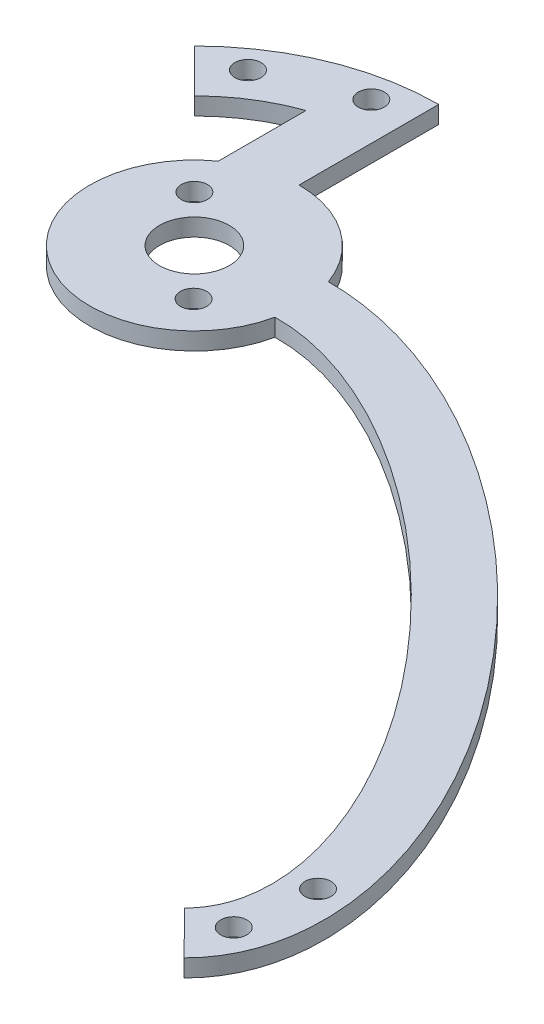
SolidWorks part; units mm, degrees
ref_plane "Спереди" through (0, 0, 0) normal (0, 0, 1) x (1, 0, 0)
ref_plane "Сверху" through (0, 0, 0) normal (0, 1, 0) x (1, 0, 0)
ref_plane "Справа" through (0, 0, 0) normal (1, 0, 0) x (0, 0, -1)
sketch "Эскиз1" plane through (0, 0, 0) normal (0, 1, 0) x (1, 0, 0)
  line L0 (0, 22) -> (0, 28)
  line L1 (65.2044, -66.3128) -> (70.1122, -71.3041)
  line L2 (0, 0) -> (-33.0408, 33.0408) construction
  line L3 (0, 12) -> (0, 22)
  line L4 (-14.8492, 14.8492) -> (-19.799, 19.799)
  line L5 (-7, 19.799) -> (-7, 9.7468)
  line L11 (0, 0) -> (70.1122, -71.3041) construction
  arc A0 (0, 28) -> (-19.799, 19.799) centre (0, 0) ccw
  arc A1 (-7, 19.799) -> (-14.8492, 14.8492) centre (0, 0) ccw
  circle A2 centre (0, 0) radius 7.5 construction
  arc A3 (-7, 9.7468) -> (11.7369, -2.4988) centre (0, 0) ccw
  arc A4 (11.2868, 4.0752) -> (0, 12) centre (0, 0) ccw
  circle A5 centre (0, 0) radius 4
  circle A6 centre (-5.3033, 5.3033) radius 1.5
  circle A7 centre (5.2584, -5.3478) radius 1.5
  ellipse E1 centre (35.0561, -35.6521) end of major axis (4.9079, -4.9913) minor radius 18 (65.2044, -66.3128) -> (11.7369, -2.4988) ccw
  ellipse E2 centre (35.0561, -35.6521) end of major axis (70.1122, -71.3041) minor radius 25 (70.1122, -71.3041) -> (11.2868, 4.0752) ccw
  dimension "D1" = 28
  dimension "D2" = 21
  dimension "D7" = 24
  dimension "D4" = 8
  dimension "D3" = 50
  dimension "D5" = 7
  dimension "D8" = 7
extrude "Бобышка-Вытянуть1" add sketch "Эскиз1" along normal blind 2
sketch "Эскиз2" plane through (0, 2, 0) normal (0, 1, 0) x (1, 0, 0)
  line L0 (0, 0) -> (0, 16.5609) construction
  line L1 (0, 0) -> (-2.989, 16.9517) construction
  line L2 (0, 0) -> (-6.9675, 16.8209) construction
  line L3 (0, 0) -> (70.1122, -71.3041) construction
  line L5 (35.0561, -35.6521) -> (89.9937, -82.5448) construction
  line L6 (35.0561, -35.6521) -> (104.5272, -76.5457) construction
  circle A0 centre (0, 0) radius 25 construction
  circle A1 centre (-4.3412, 24.6202) radius 1.5
  circle A2 centre (-14.3394, 20.4788) radius 1.5
  circle A3 centre (70.9507, -56.7811) radius 1.5
  circle A4 centre (69.9401, -65.4278) radius 1.5
  ellipse E0 centre (35.0561, -35.6521) end of major axis (67.6583, -68.8085) minor radius 21.5 construction
  dimension "D2" = 22.5
  dimension "D3" = 50
  dimension "D4" = 3
  dimension "D1" = 10
  dimension "D5" = 5
  dimension "D6" = 15
extrude "Вырез-Вытянуть2" cut sketch "Эскиз2" against normal through all
